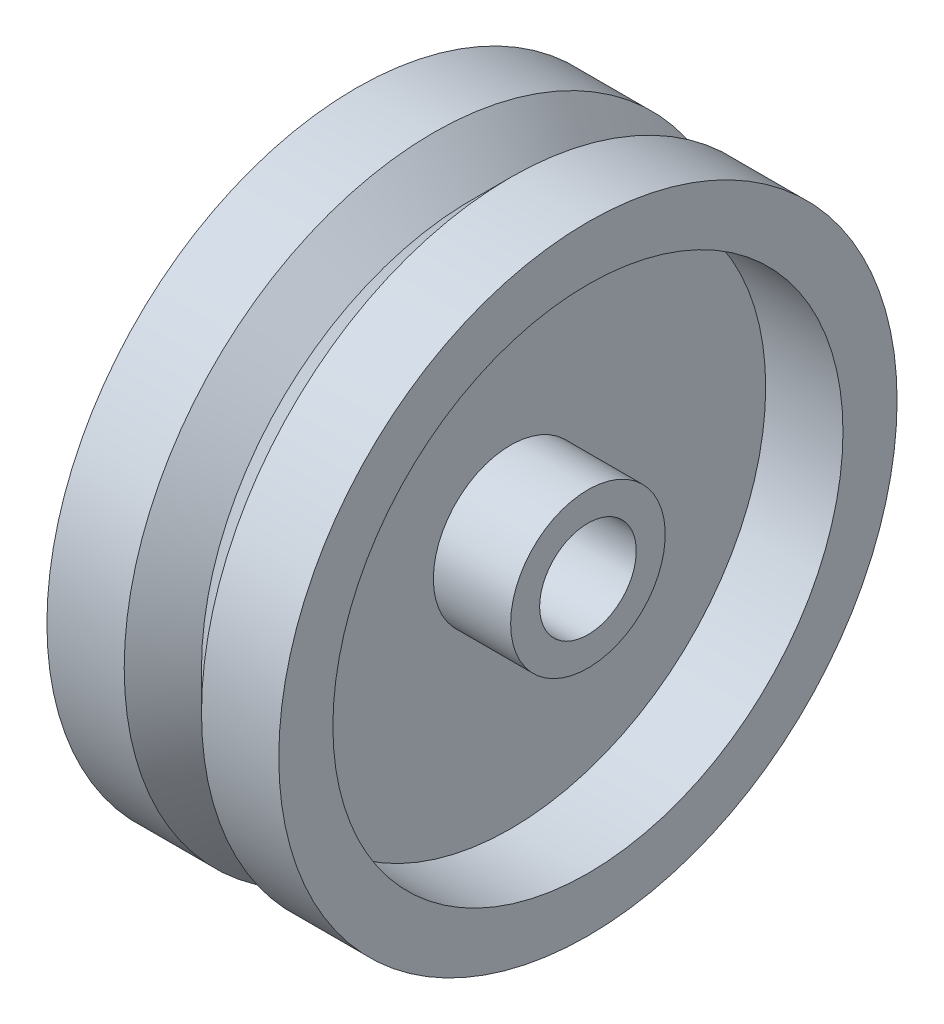
SolidWorks part; units mm, degrees
ref_plane "Front Plane" through (0, 0, 0) normal (0, 0, 1) x (1, 0, 0)
ref_plane "Top Plane" through (0, 0, 0) normal (0, 1, 0) x (1, 0, 0)
ref_plane "Right Plane" through (0, 0, 0) normal (1, 0, 0) x (0, 0, -1)
sketch "Sketch2" plane through (0, 0, 0) normal (0, 0, 1) x (1, 0, 0)
  line L31 (-11.3672, 0) -> (21.072, 0) construction
  line L32 (-7.5, 3.125) -> (7.5, 3.125)
  line L33 (7.5, 3.125) -> (7.5, 5)
  line L34 (7.5, 5) -> (2.5, 5)
  line L35 (2.5, 5) -> (2.5, 16.5)
  line L36 (2.5, 16.5) -> (7.5, 16.5)
  line L37 (7.5, 16.5) -> (7.5, 20)
  line L38 (7.5, 20) -> (2.5, 20)
  line L39 (2.5, 20) -> (0, 17.5)
  line L40 (0, 17.5) -> (-2.5, 20)
  line L41 (-2.5, 20) -> (-7.5, 20)
  line L42 (-7.5, 20) -> (-7.5, 16.5)
  line L43 (-7.5, 16.5) -> (-2.5, 16.5)
  line L44 (-2.5, 16.5) -> (-2.5, 5)
  line L45 (-2.5, 5) -> (-7.5, 5)
  line L46 (-7.5, 5) -> (-7.5, 3.125)
  line L48 (0, 0) -> (0, 27.6327) construction
  point P13 (0, 0)
  point P22 (0, 0)
  point P23 (0, 0)
  point P24 (0, 0)
  point P25 (0, 0)
  point P26 (0, 0)
  dimension "D1" = 6.25
  dimension "D2" = 10
  dimension "D3" = 40
  dimension "D4" = 33
  dimension "D5" = 90
  dimension "D6" = 15
  dimension "D7" = 5
revolve "Revolve2" add sketch "Sketch2" angle 360 about L31
